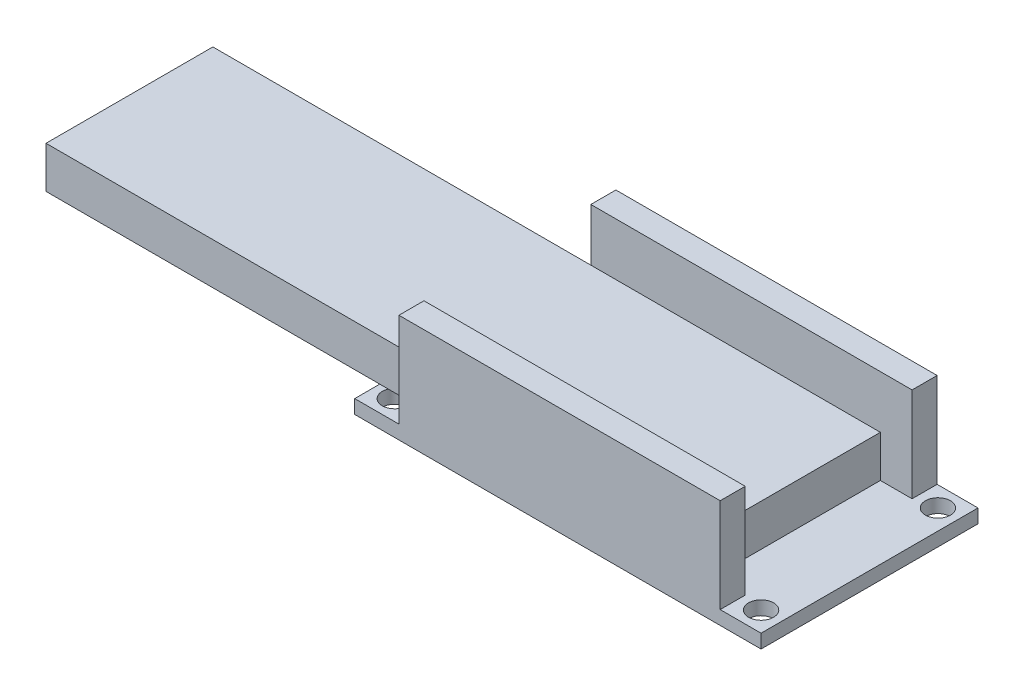
SolidWorks part; units mm, degrees
ref_plane "Front Plane" through (0, 0, 0) normal (0, 0, 1) x (1, 0, 0)
ref_plane "Top Plane" through (0, 0, 0) normal (0, 1, 0) x (1, 0, 0)
ref_plane "Right Plane" through (0, 0, 0) normal (1, 0, 0) x (0, 0, -1)
sketch "Sketch1" plane through (0, 0, 0) normal (0, 1, 0) x (1, 0, 0)
  line L0 (0, 0) -> (0, 6.7767) construction
  line L1 (-24.35, 13) -> (24.35, 13)
  line L2 (-24.35, 13) -> (-24.35, -13)
  line L3 (-24.35, -13) -> (24.35, -13)
  line L4 (24.35, 13) -> (24.35, -13)
  line L5 (-24.35, 13) -> (24.35, -13) construction
  line L6 (-24.35, -13) -> (24.35, 13) construction
  line L7 (0, 0) -> (9.7166, 0) construction
  circle A0 centre (-21.95, 10.6) radius 1.5
  circle A1 centre (-21.95, -10.6) radius 1.5
  circle A2 centre (21.95, -10.6) radius 1.5
  circle A3 centre (21.95, 10.6) radius 1.5
  point P0 (0, 0)
  dimension "D3" = 3
  dimension "D6" = 0.9
  dimension "D7" = 0.9
  dimension "D8" = 0.9
  dimension "D1" = 26
  dimension "D2" = 48.7
  dimension "D4" = 0.9
  dimension "D5" = 0.9
extrude "Boss-Extrude1" add sketch "Sketch1" along normal blind 1.65
sketch "Sketch2" plane through (0, 1.65, 0) normal (0, 1, 0) x (1, 0, 0)
  line L0 (24.35, 13) -> (-24.35, 13) construction
  line L1 (-19.05, 13) -> (19.45, 13)
  line L2 (-19.05, 13) -> (-19.05, 10)
  line L3 (-19.05, 10) -> (19.45, 10)
  line L4 (19.45, 13) -> (19.45, 10)
  line L5 (-24.35, 13) -> (-24.35, -13) construction
  line L6 (0, 0) -> (9.6057, 0) construction
  line L7 (19.45, -13) -> (19.45, -10)
  line L8 (-19.05, -13) -> (19.45, -13)
  line L9 (-19.05, -10) -> (19.45, -10)
  line L10 (-19.05, -13) -> (-19.05, -10)
  line L11 (-24.35, -13) -> (24.35, -13) construction
  dimension "D1" = 5.3
  dimension "D2" = 38.5
  dimension "D3" = 3
  dimension "D4" = 3
  dimension "D5" = 38.5
  dimension "D6" = 5.3
extrude "Boss-Extrude2" add sketch "Sketch2" along normal blind 11.3
sketch "Sketch3" plane through (0, 1.65, 0) normal (0, 1, 0) x (1, 0, 0)
  line L0 (-24.35, 13) -> (-24.35, -13) construction
  line L1 (-64.35, 10) -> (15.65, 10)
  line L2 (-64.35, 10) -> (-64.35, -10)
  line L3 (-64.35, -10) -> (15.65, -10)
  line L4 (15.65, 10) -> (15.65, -10)
  line L5 (-64.35, 10) -> (15.65, -10) construction
  line L6 (-64.35, -10) -> (15.65, 10) construction
  point P0 (-24.35, 0)
  dimension "D1" = 40
  dimension "D2" = 20
extrude "Boss-Extrude3" add sketch "Sketch3" along normal blind 5
